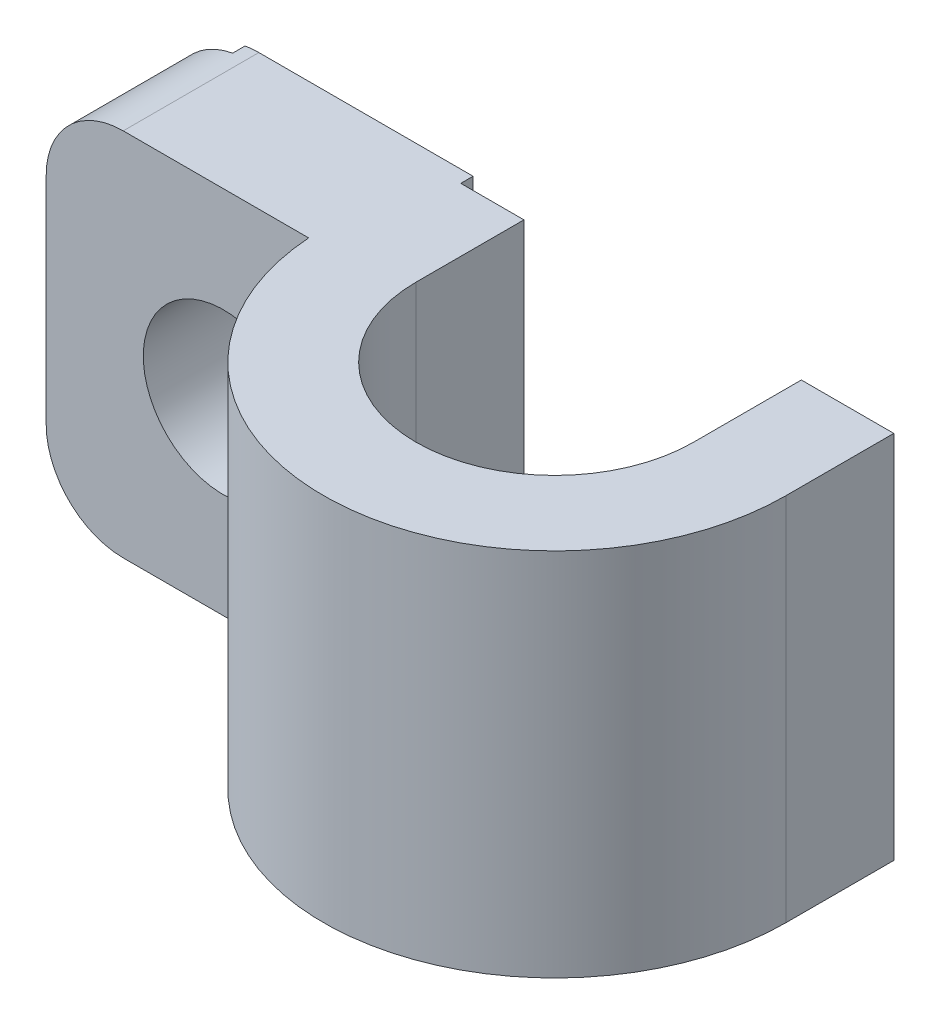
SolidWorks part; units mm, degrees
ref_plane "Спереди" through (0, 0, 0) normal (0, 0, 1) x (1, 0, 0)
ref_plane "Сверху" through (0, 0, 0) normal (0, 1, 0) x (1, 0, 0)
ref_plane "Справа" through (0, 0, 0) normal (1, 0, 0) x (0, 0, -1)
sketch "Эскиз1" plane through (0, 0, 0) normal (0, 0, 1) x (1, 0, 0)
  line L1 (0, 0) -> (12, 0)
  line L2 (0, 0) -> (0, 12)
  line L3 (0, 12) -> (12, 12)
  line L4 (12, 0) -> (12, 12)
  dimension "D1" = 12
  dimension "D2" = 12
extrude "Бобышка-Вытянуть1" add sketch "Эскиз1" along normal blind 4
sketch "Эскиз2" plane through (0, 12, 0) normal (0, 1, 0) x (1, 0, 0)
  line L0 (8.5, 0) -> (23.5, 0)
  line L5 (8.5, 0) -> (8.5, -3.5)
  line L8 (23.5, 0) -> (23.5, -3.5)
  line L9 (12, 0) -> (0, 0) construction
  arc A1 (8.5, -3.5) -> (23.5, -3.5) centre (16, -3.5) ccw
  circle A2 centre (16, -3.5) radius 4.5 construction
  point P0 (16, -3.5)
  point P2 (32, 0)
  point P4 (29.7815, 1.4619)
  point P6 (6, 0)
  dimension "D1" = 3
  dimension "D3" = 9
  dimension "D4" = 10
  dimension "D2" = 3.5
extrude "Бобышка-Вытянуть2" add sketch "Эскиз2" against normal up to surface (12 mm away) up to face at (6, 0, 2)
sketch "Эскиз6" plane through (0, 12, 0) normal (0, 1, 0) x (1, 0, 0)
  line L0 (11.5, -3.5) -> (11.5, 0)
  line L1 (23.5, 0) -> (0, 0) construction
  line L2 (11.5, 0) -> (20.5, 0)
  line L3 (20.5, 0) -> (20.5, -3.5)
  arc A0 (11.5, -3.5) -> (20.5, -3.5) centre (16, -3.5) ccw
  arc A1 (8.5167, -4) -> (23.5, -3.5) centre (16, -3.5) ccw construction
  dimension "D1" = 3
extrude "Вырез-Вытянуть3" cut sketch "Эскиз6" against normal through all
sketch "Эскиз5" plane through (0, 0, 0) normal (0, 0, -1) x (-1, 0, 0)
  line L0 (0, 0) -> (-11.5, 0) construction
  line L1 (-2.05, 0) -> (-9.45, 0)
  line L2 (-2.05, 0) -> (-2.05, 12)
  line L3 (-2.05, 12) -> (-9.45, 12)
  line L4 (-9.45, 0) -> (-9.45, 12)
  line L5 (-11.5, 12) -> (0, 12) construction
  line L7 (-11.5, 12) -> (0, 12) construction
  point P10 (-5.75, 12)
  point P11 (-5.75, 12)
  dimension "D1" = 7.4
extrude "Бобышка-Вытянуть3" add sketch "Эскиз5" along normal blind 0.4
sketch "Эскиз3" plane through (0, 0, 4) normal (0, 0, 1) x (1, 0, 0)
  line L0 (0, 12) -> (0, 0) construction
  line L1 (9.45, 0) -> (2.05, 0) construction
  circle A0 centre (5.75, 6) radius 2.6
  point P4 (0, 6)
  point P7 (5.75, 0)
  dimension "D1" = 5.2
extrude "Вырез-Вытянуть1" cut sketch "Эскиз3" against normal through all
sketch "Эскиз4" plane through (0, 0, 4) normal (0, 0, 1) x (1, 0, 0)
  circle A0 centre (5.75, 6) radius 5
  dimension "D1" = 10
extrude "Вырез-Вытянуть2" cut sketch "Эскиз4" along normal through all
fillet "Скругление1" radius 2.5 2 edges at (0, 12, 2) (0, 0, 2)
